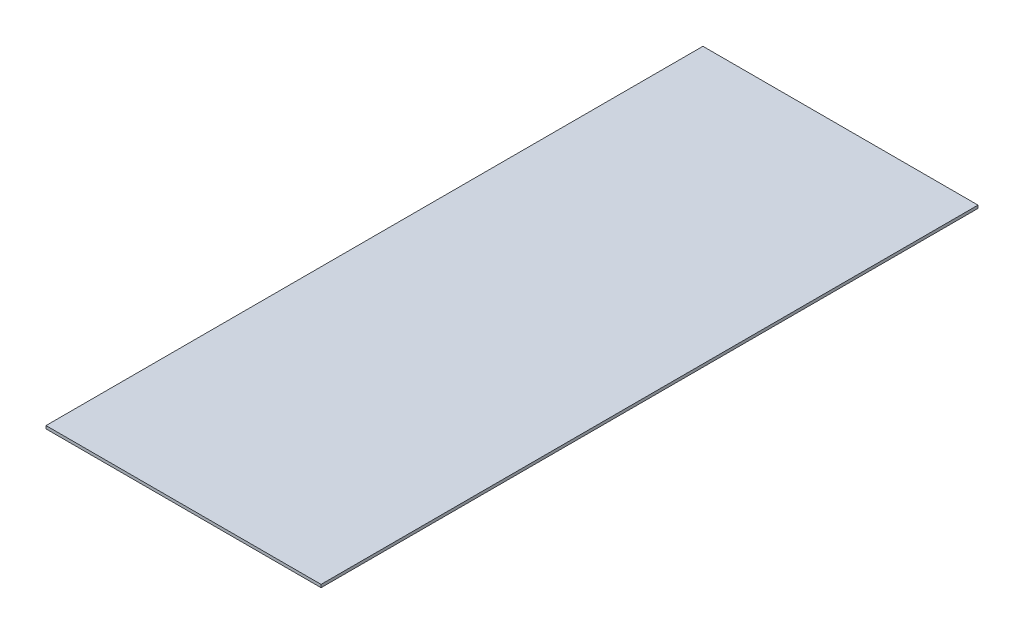
SolidWorks part; units mm, degrees
material "Epoxy, Unfilled"
ref_plane "Front Plane" through (0, 0, 0) normal (0, 0, 1) x (1, 0, 0)
ref_plane "Top Plane" through (0, 0, 0) normal (0, 1, 0) x (1, 0, 0)
ref_plane "Right Plane" through (0, 0, 0) normal (1, 0, 0) x (0, 0, -1)
sketch "Sketch1" plane through (0, 0, 0) normal (0, 1, 0) x (1, 0, 0)
  line L1 (0, 0) -> (17, 0)
  line L2 (0, 0) -> (0, 40.6)
  line L3 (0, 40.6) -> (17, 40.6)
  line L4 (17, 0) -> (17, 40.6)
extrude "Boss-Extrude1" add sketch "Sketch1" along normal blind 0.18
